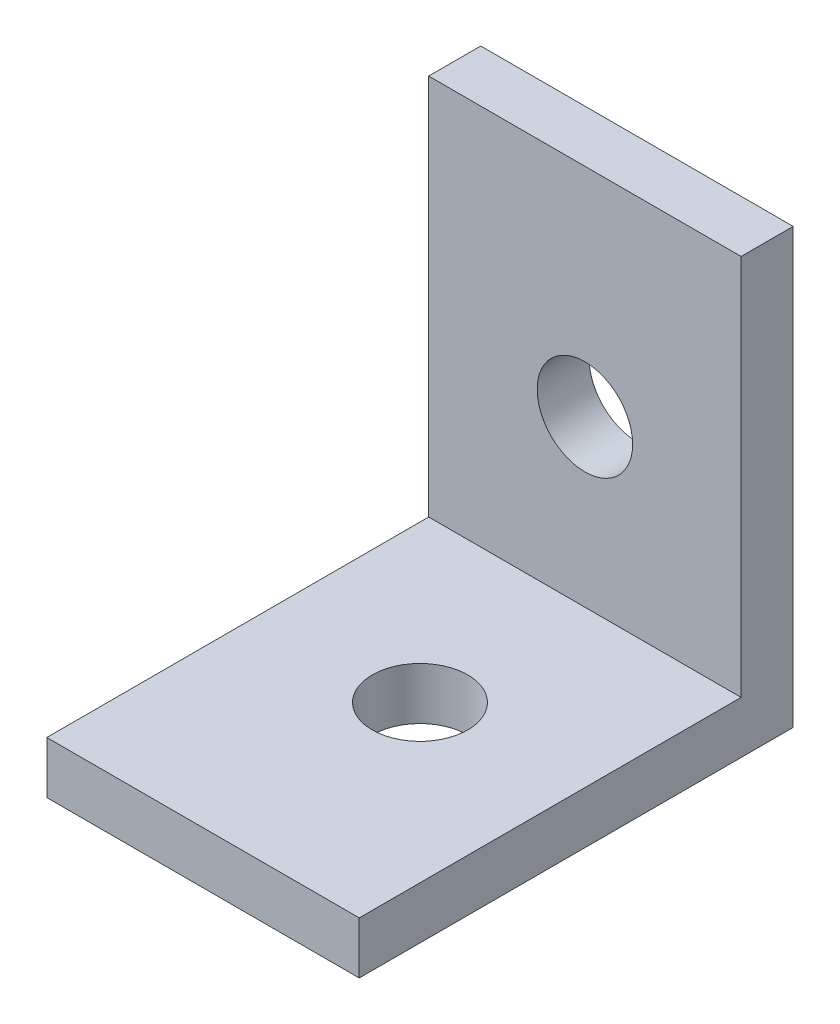
SolidWorks part; units mm, degrees
ref_plane "前视基准面" through (0, 0, 0) normal (0, 0, 1) x (1, 0, 0)
ref_plane "上视基准面" through (0, 0, 0) normal (0, 1, 0) x (1, 0, 0)
ref_plane "右视基准面" through (0, 0, 0) normal (1, 0, 0) x (0, 0, -1)
sketch "草图1" plane through (0, 0, 0) normal (0, 1, 0) x (1, 0, 0)
  line L1 (-9, 12.5) -> (9, 12.5)
  line L2 (-9, 12.5) -> (-9, -12.5)
  line L3 (-9, -12.5) -> (9, -12.5)
  line L4 (9, 12.5) -> (9, -12.5)
  line L5 (-9, 12.5) -> (9, -12.5) construction
  line L6 (-9, -12.5) -> (9, 12.5) construction
  circle A0 centre (0, 0) radius 2.75
  point P0 (0, 0)
  dimension "D3" = 5.5
  dimension "D1" = 25
  dimension "D2" = 18
extrude "凸台-拉伸1" add sketch "草图1" along normal blind 3
ref_plane "基准面1" through (0, 3, 0) normal (0, 1, 0) x (1, 0, 0)
sketch "草图2" plane through (0, 3, 0) normal (0, 1, 0) x (1, 0, 0)
  line L0 (9, -12.5) -> (9, 12.5) construction
  line L1 (-9, 12.5) -> (9, 12.5)
  line L2 (-9, 12.5) -> (-9, 9.5)
  line L3 (-9, 9.5) -> (9, 9.5)
  line L4 (9, 12.5) -> (9, 9.5)
  dimension "D1" = 3
extrude "凸台-拉伸2" add sketch "草图2" along normal blind 22
ref_plane "基准面2" through (0, 0, -9.5) normal (0, 0, 1) x (1, 0, 0)
sketch "草图3" plane through (0, 0, -9.5) normal (0, 0, 1) x (1, 0, 0)
  line L0 (0, 25) -> (0, 0) construction
  line L1 (-9, 25) -> (9, 25) construction
  circle A0 centre (0, 12.5) radius 2.75
  dimension "D1" = 5.5
extrude "切除-拉伸1" cut sketch "草图3" against normal blind 22
